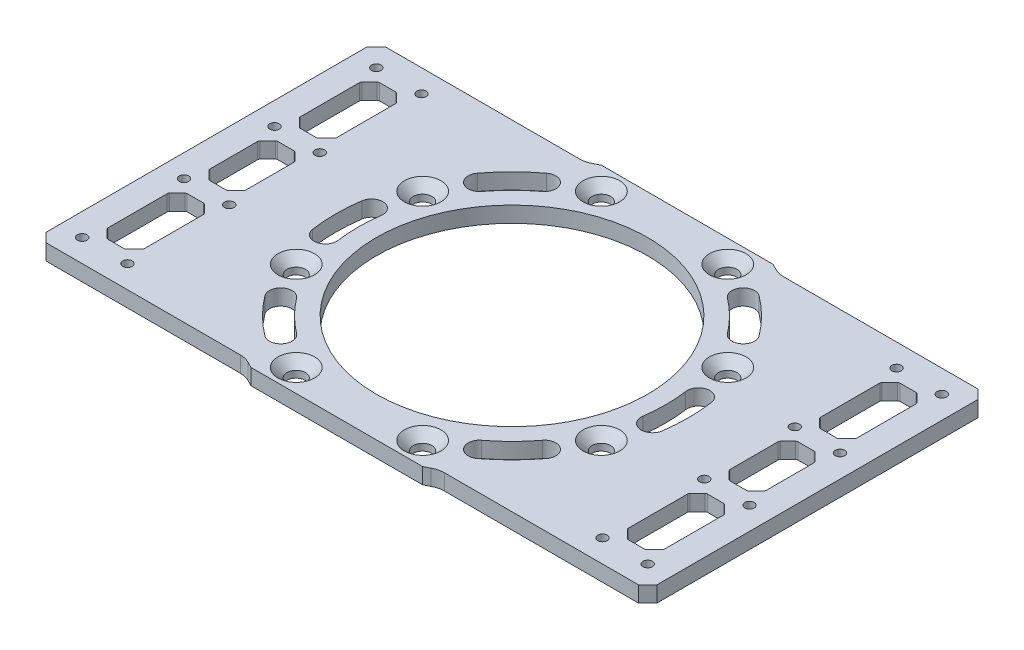
SolidWorks part; units mm, degrees
ref_plane "前视基准面" through (0, 0, 0) normal (0, 0, 1) x (1, 0, 0)
ref_plane "上视基准面" through (0, 0, 0) normal (0, 1, 0) x (1, 0, 0)
ref_plane "右视基准面" through (0, 0, 0) normal (1, 0, 0) x (0, 0, -1)
sketch "草图1" plane through (0, 0, 0) normal (0, 1, 0) x (1, 0, 0)
  line L0 (-125, -20) -> (-105, -20) construction
  line L1 (135, -77.4432) -> (-135, -77.4432)
  line L2 (135, -77.4432) -> (135, 77.4432)
  line L3 (135, 77.4432) -> (-135, 77.4432)
  line L4 (-135, -77.4432) -> (-135, 77.4432)
  line L5 (135, -77.4432) -> (-135, 77.4432) construction
  line L6 (135, 77.4432) -> (-135, -77.4432) construction
  line L7 (-105, -65) -> (-125, -65) construction
  line L8 (-105, -65) -> (-105, 65) construction
  line L9 (-105, 65) -> (-125, 65) construction
  line L10 (-125, -65) -> (-125, 65) construction
  line L11 (-105, -65) -> (-125, 65) construction
  line L12 (-105, 65) -> (-125, -65) construction
  line L13 (-125, 20) -> (-105, 20) construction
  line L14 (0, 77.4432) -> (0, -77.4432) construction
  circle A0 centre (0, 0) radius 73 construction
  circle A1 centre (-67.4432, -27.9359) radius 4.1
  circle A2 centre (-67.4432, 27.9359) radius 4.1
  circle A3 centre (-27.9359, 67.4432) radius 4.1
  circle A4 centre (27.9359, 67.4432) radius 4.1
  circle A5 centre (67.4432, 27.9359) radius 4.1
  circle A6 centre (67.4432, -27.9359) radius 4.1
  circle A7 centre (27.9359, -67.4432) radius 4.1
  circle A8 centre (-27.9359, -67.4432) radius 4.1
  circle A9 centre (0, 0) radius 60
  circle A10 centre (-125, 65) radius 2.1
  circle A11 centre (-105, 65) radius 2.1
  circle A12 centre (-125, -65) radius 2.1
  circle A13 centre (-105, -65) radius 2.1
  circle A14 centre (-125, 20) radius 2.1
  circle A15 centre (-105, 20) radius 2.1
  circle A16 centre (-125, -20) radius 2.1
  circle A17 centre (-105, -20) radius 2.1
  circle A18 centre (105, -65) radius 2.1
  circle A19 centre (125, -65) radius 2.1
  circle A20 centre (105, -20) radius 2.1
  circle A21 centre (125, -20) radius 2.1
  circle A22 centre (105, 20) radius 2.1
  circle A23 centre (125, 20) radius 2.1
  circle A24 centre (105, 65) radius 2.1
  circle A25 centre (125, 65) radius 2.1
  point P22 (0, 0)
  point P27 (-115, 0)
  dimension "D1" = 146
  dimension "D2" = 8.2
  dimension "D4" = 120
  dimension "D10" = 4.2
  dimension "D5" = 10
  dimension "D6" = 10
  dimension "D7" = 130
  dimension "D8" = 20
  dimension "D9" = 20
  dimension "D12" = 20
  dimension "D11" = 230
  dimension "D3" = 8
extrude "凸台-拉伸1" add sketch "草图1" along normal mid plane 7
sketch "草图2" plane through (0, 3.5, 0) normal (0, 1, 0) x (1, 0, 0)
  line L0 (-135, 75) -> (-42.5627, 75)
  line L1 (-135, 77.4432) -> (-135, -77.4432) construction
  line L3 (135, 77.4432) -> (-135, 77.4432) construction
  line L4 (-37.9359, 77.4432) -> (-135, 77.4432)
  line L5 (-135, 77.4432) -> (-135, 75)
  line L6 (0, 0) -> (0, 50000) construction
  line L7 (0, 0) -> (50000, 0) construction
  line L8 (135, 77.4432) -> (135, 75)
  line L9 (37.9359, 77.4432) -> (135, 77.4432)
  line L10 (135, 75) -> (42.5627, 75)
  line L11 (135, -75) -> (42.5627, -75)
  line L12 (37.9359, -77.4432) -> (135, -77.4432)
  line L13 (135, -77.4432) -> (135, -75)
  line L14 (-135, -77.4432) -> (-135, -75)
  line L15 (-37.9359, -77.4432) -> (-135, -77.4432)
  line L16 (-135, -75) -> (-42.5627, -75)
  circle A0 centre (-105, 65) radius 2.1 construction
  arc A2 (-37.9359, 77.4432) -> (-42.5627, 75) centre (0, 0) ccw
  circle A3 centre (-27.9359, 67.4432) radius 4.1 construction
  arc A4 (37.9359, 77.4432) -> (42.5627, 75) centre (0, 0) cw
  arc A5 (37.9359, -77.4432) -> (42.5627, -75) centre (0, 0) ccw
  arc A6 (-37.9359, -77.4432) -> (-42.5627, -75) centre (0, 0) cw
  dimension "D1" = 10
  dimension "D2" = 10
extrude "切除-拉伸1" cut sketch "草图2" against normal through all
chamfer "倒角1" distance 4 angle 45 12 edges at (-27.9359, 3.5, -63.3432) (27.9359, 3.5, -63.3432) (67.4432, 3.5, -23.8359) (67.4432, 3.5, 32.0359) (27.9359, 3.5, 71.5432) (-27.9359, 3.5, 71.5432) (-67.4432, 3.5, 32.0359) (-67.4432, 3.5, -23.8359) (135, 0, -75) (135, 0, 75) (-135, 0, 75) (-135, 0, -75)
fillet "圆角1" radius 10 4 edges at (42.5627, 0, -75) (-42.5627, 0, -75) (42.5627, 0, 75) (-42.5627, 0, 75)
sketch "草图3" plane through (0, 3.5, 0) normal (0, 1, 0) x (1, 0, 0)
  line L0 (0, 77.4432) -> (0, -77.4432) construction
  line L1 (-107, 25) -> (-123, 25)
  line L2 (-107, 25) -> (-107, 60)
  line L3 (-107, 60) -> (-123, 60)
  line L4 (-123, 25) -> (-123, 60)
  line L5 (-107, 25) -> (-123, 60) construction
  line L6 (-107, 60) -> (-123, 25) construction
  line L7 (-107, -15) -> (-123, -15)
  line L8 (-107, -15) -> (-107, 15)
  line L9 (-107, 15) -> (-123, 15)
  line L10 (-123, -15) -> (-123, 15)
  line L11 (-107, -15) -> (-123, 15) construction
  line L12 (-107, 15) -> (-123, -15) construction
  line L13 (-107, -60) -> (-123, -60)
  line L14 (-107, -60) -> (-107, -25)
  line L15 (-107, -25) -> (-123, -25)
  line L16 (-123, -60) -> (-123, -25)
  line L17 (-107, -60) -> (-123, -25) construction
  line L18 (-107, -25) -> (-123, -60) construction
  line L19 (37.9359, 77.4432) -> (-37.9359, 77.4432) construction
  line L20 (-37.9359, -77.4432) -> (37.9359, -77.4432) construction
  line L21 (107, -25) -> (123, -25)
  line L22 (123, -60) -> (123, -25)
  line L23 (107, -60) -> (123, -60)
  line L24 (107, -60) -> (107, -25)
  line L25 (107, 15) -> (123, 15)
  line L26 (123, -15) -> (123, 15)
  line L27 (107, -15) -> (123, -15)
  line L28 (107, -15) -> (107, 15)
  line L29 (107, 60) -> (123, 60)
  line L30 (123, 25) -> (123, 60)
  line L31 (107, 25) -> (123, 25)
  line L32 (107, 25) -> (107, 60)
  circle A3 centre (-125, -20) radius 2.1 construction
  circle A4 centre (-125, 65) radius 2.1 construction
  circle A5 centre (-125, 20) radius 2.1 construction
  circle A6 centre (-105, -20) radius 2.1 construction
  point P0 (-115, 42.5)
  point P5 (-115, 0)
  point P10 (-115, -42.5)
  dimension "D1" = 22.5
  dimension "D6" = 5
  dimension "D2" = 10
  dimension "D3" = 22.5
  dimension "D4" = 20
  dimension "D5" = 2
  dimension "D7" = 5
extrude "切除-拉伸2" cut sketch "草图3" against normal through all
chamfer "倒角2" distance 4 angle 45 24 edges at (107, 0, -60) (123, 0, -60) (107, 0, -25) (123, 0, -25) (107, 0, -15) (107, 0, 15) (123, 0, 15) (123, 0, -15) (107, 0, 25) (123, 0, 25) (123, 0, 60) (107, 0, 60) (-123, 0, 60) (-107, 0, 60) (-107, 0, 25) (-123, 0, 25) (-123, 0, 15) (-107, 0, 15) (-107, 0, -15) (-123, 0, -15) (-123, 0, -25) (-107, 0, -25) (-107, 0, -60) (-123, 0, -60)
fillet "圆角2" radius 1 48 edges at (123, 0, 56) (119, 0, 60) (111, 0, 60) (107, 0, 56) (107, 0, 29) (111, 0, 25) (123, 0, 29) (119, 0, 25) (123, 0, 11) (119, 0, 15) (111, 0, 15) (107, 0, 11) (107, 0, -11) (111, 0, -15) (123, 0, -11) (119, 0, -15) (123, 0, -29) (119, 0, -25) (111, 0, -25) (107, 0, -29) (107, 0, -56) (111, 0, -60) (123, 0, -56) (119, 0, -60) (-107, 0, 56) (-111, 0, 60) (-119, 0, 60) (-123, 0, 56) (-123, 0, 29) (-119, 0, 25) (-107, 0, 29) (-111, 0, 25) (-107, 0, 11) (-111, 0, 15) (-119, 0, 15) (-123, 0, 11) (-123, 0, -11) (-119, 0, -15) (-107, 0, -11) (-111, 0, -15) (-123, 0, -29) (-119, 0, -25) (-111, 0, -25) (-107, 0, -29) (-107, 0, -56) (-123, 0, -56) (-119, 0, -60) (-111, 0, -60)
sketch "草图4" plane through (0, 3.5, 0) normal (0, 1, 0) x (1, 0, 0)
  line L0 (-73, 0) -> (0, 0) construction
  line L1 (0, 0) -> (-72.2896, -10.1596) construction
  line L2 (0, 0) -> (-58.3004, 43.9325) construction
  arc A0 (-72.2896, -10.1596) -> (-72.2896, 10.1596) centre (0, 0) cw construction
  arc A1 (-77.2409, 10.8555) -> (-77.2409, -10.8555) centre (0, 0) ccw
  arc A2 (-67.3382, 9.4638) -> (-67.3382, -9.4638) centre (0, 0) ccw
  arc A3 (-67.3382, 9.4638) -> (-77.2409, 10.8555) centre (-72.2896, 10.1596) ccw
  arc A4 (-77.2409, -10.8555) -> (-67.3382, -9.4638) centre (-72.2896, -10.1596) ccw
  circle A5 centre (0, 0) radius 60 construction
  arc A6 (-58.3004, 43.9325) -> (-43.9325, 58.3004) centre (0, 0) cw construction
  arc A7 (-46.9416, 62.2936) -> (-62.2936, 46.9416) centre (0, 0) ccw
  arc A8 (-40.9234, 54.3072) -> (-54.3072, 40.9234) centre (0, 0) ccw
  arc A9 (-40.9234, 54.3072) -> (-46.9416, 62.2936) centre (-43.9325, 58.3004) ccw
  arc A10 (-62.2936, 46.9416) -> (-54.3072, 40.9234) centre (-58.3004, 43.9325) ccw
  arc A16 (43.9325, 58.3004) -> (58.3004, 43.9325) centre (0, 0) cw construction
  arc A17 (62.2936, 46.9416) -> (46.9416, 62.2936) centre (0, 0) ccw
  arc A18 (54.3072, 40.9234) -> (40.9234, 54.3072) centre (0, 0) ccw
  arc A19 (54.3072, 40.9234) -> (62.2936, 46.9416) centre (58.3004, 43.9325) ccw
  arc A20 (46.9416, 62.2936) -> (40.9234, 54.3072) centre (43.9325, 58.3004) ccw
  arc A21 (72.2896, 10.1596) -> (72.2896, -10.1596) centre (0, 0) cw construction
  arc A22 (77.2409, -10.8555) -> (77.2409, 10.8555) centre (0, 0) ccw
  arc A23 (67.3382, -9.4638) -> (67.3382, 9.4638) centre (0, 0) ccw
  arc A24 (67.3382, -9.4638) -> (77.2409, -10.8555) centre (72.2896, -10.1596) ccw
  arc A25 (77.2409, 10.8555) -> (67.3382, 9.4638) centre (72.2896, 10.1596) ccw
  arc A26 (58.3004, -43.9325) -> (43.9325, -58.3004) centre (0, 0) cw construction
  arc A27 (46.9416, -62.2936) -> (62.2936, -46.9416) centre (0, 0) ccw
  arc A28 (40.9234, -54.3072) -> (54.3072, -40.9234) centre (0, 0) ccw
  arc A29 (40.9234, -54.3072) -> (46.9416, -62.2936) centre (43.9325, -58.3004) ccw
  arc A30 (62.2936, -46.9416) -> (54.3072, -40.9234) centre (58.3004, -43.9325) ccw
  arc A36 (-43.9325, -58.3004) -> (-58.3004, -43.9325) centre (0, 0) cw construction
  arc A37 (-62.2936, -46.9416) -> (-46.9416, -62.2936) centre (0, 0) ccw
  arc A38 (-54.3072, -40.9234) -> (-40.9234, -54.3072) centre (0, 0) ccw
  arc A39 (-54.3072, -40.9234) -> (-62.2936, -46.9416) centre (-58.3004, -43.9325) ccw
  arc A40 (-46.9416, -62.2936) -> (-40.9234, -54.3072) centre (-43.9325, -58.3004) ccw
  arc A111 (-10.1596, 72.2896) -> (10.1596, 72.2896) centre (0, 0) cw construction
  arc A112 (10.8555, 77.2409) -> (-10.8555, 77.2409) centre (0, 0) ccw
  arc A113 (9.4638, 67.3382) -> (-9.4638, 67.3382) centre (0, 0) ccw
  arc A114 (9.4638, 67.3382) -> (10.8555, 77.2409) centre (10.1596, 72.2896) ccw
  arc A115 (-10.8555, 77.2409) -> (-9.4638, 67.3382) centre (-10.1596, 72.2896) ccw
  arc A116 (10.1596, -72.2896) -> (-10.1596, -72.2896) centre (0, 0) cw construction
  arc A117 (-10.8555, -77.2409) -> (10.8555, -77.2409) centre (0, 0) ccw
  arc A118 (-9.4638, -67.3382) -> (9.4638, -67.3382) centre (0, 0) ccw
  arc A119 (-9.4638, -67.3382) -> (-10.8555, -77.2409) centre (-10.1596, -72.2896) ccw
  arc A120 (10.8555, -77.2409) -> (9.4638, -67.3382) centre (10.1596, -72.2896) ccw
  point P4 (-73, 0)
  point P18 (-51.6188, 51.6188)
  point P25 (0, 73)
  point P32 (51.6188, 51.6188)
  point P39 (73, 0)
  point P46 (51.6188, -51.6188)
  point P53 (0, -73)
  point P60 (-51.6188, -51.6188)
  point P71 (0, 73)
  point P79 (0, -73)
  point P87 (0, 73)
  point P95 (0, -73)
  point P103 (0, 73)
  point P111 (0, -73)
  point P119 (0, 73)
  point P127 (0, -73)
  point P135 (0, 73)
  point P143 (0, -73)
  point P151 (0, 73)
  point P159 (0, -73)
  point P167 (0, 73)
  point P175 (0, -73)
  point P183 (0, 73)
  point P191 (0, -73)
  dimension "D1" = 73
  dimension "D2" = 8
  dimension "D3" = 8
  dimension "D5" = 45
  dimension "D6" = 45
  dimension "D4" = 8
extrude "切除-拉伸3" cut sketch "草图4" against normal blind 7
equation "\"D9@草图1\"=\"D8@草图1\""
